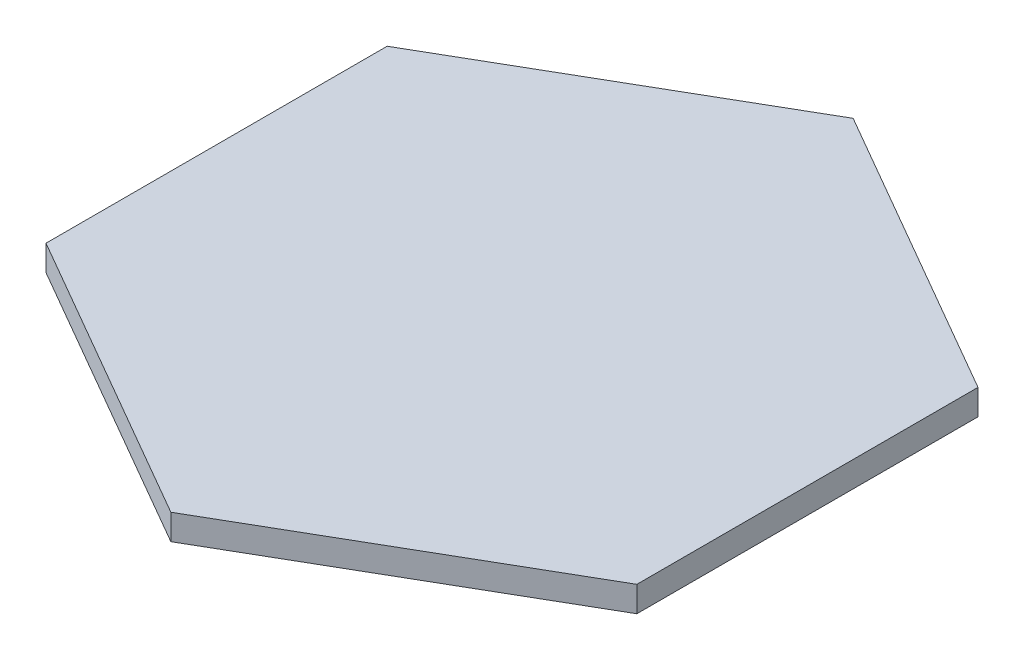
SolidWorks part; units mm, degrees
ref_plane "Plan de face" through (0, 0, 0) normal (0, 0, 1) x (1, 0, 0)
ref_plane "Plan de dessus" through (0, 0, 0) normal (0, 1, 0) x (1, 0, 0)
ref_plane "Plan de droite" through (0, 0, 0) normal (1, 0, 0) x (0, 0, -1)
sketch "Esquisse1" plane through (0, 0, 0) normal (0, 1, 0) x (1, 0, 0)
  line L0 (440, -254.0341) -> (440, 254.0341)
  line L1 (0, 508.0682) -> (-440, 254.0341)
  line L2 (-440, 254.0341) -> (-440, -254.0341)
  line L3 (-440, -254.0341) -> (0, -508.0682)
  line L4 (0, -508.0682) -> (440, -254.0341)
  line L5 (440, 254.0341) -> (0, 508.0682)
  circle A0 centre (0, 0) radius 440 construction
  dimension "D1" = 880
extrude "Boss.-Extru.1" add sketch "Esquisse1" along normal blind 38
